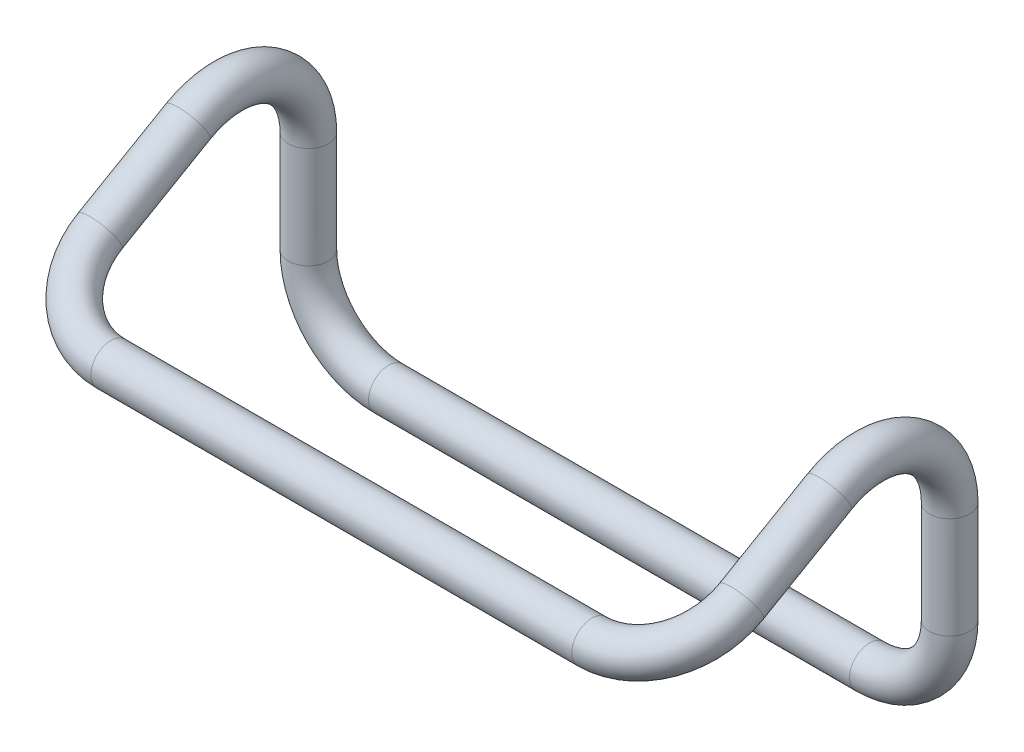
SolidWorks part; units mm, degrees
ref_plane "前视基准面" through (0, 0, 0) normal (0, 0, 1) x (1, 0, 0)
ref_plane "上视基准面" through (0, 0, 0) normal (0, 1, 0) x (1, 0, 0)
ref_plane "右视基准面" through (0, 0, 0) normal (1, 0, 0) x (0, 0, -1)
other "Configuration Table"
sketch3d "3D草图2"
  line L0 (20, 0, 0) -> (140, 0, 0)
  line L1 (160, 10, -17.3205) -> (160, 22.6795, -39.282)
  line L2 (160, 5.359, -69.282) -> (160, -20, -69.282)
  line L3 (140, -40, -69.282) -> (20, -40, -69.282)
  line L4 (0, -20, -69.282) -> (0, 5.359, -69.282)
  line L5 (0, 22.6795, -39.282) -> (0, 10, -17.3205)
  arc A0 (0, 5.359, -69.282) -> (0, 22.6795, -39.282) centre (0, 5.359, -49.282) ccw
  arc A1 (20, -40, -69.282) -> (0, -20, -69.282) centre (20, -20, -69.282) ccw
  arc A2 (160, -20, -69.282) -> (140, -40, -69.282) centre (140, -20, -69.282) ccw
  arc A3 (160, 22.6795, -39.282) -> (160, 5.359, -69.282) centre (160, 5.359, -49.282) ccw
  arc A4 (140, 0, 0) -> (160, 10, -17.3205) centre (140, 10, -17.3205) ccw
  arc A5 (20, 0, 0) -> (0, 10, -17.3205) centre (20, 10, -17.3205) ccw
  point P7 (0, 0, 0)
  point P10 (0, 40, -69.282)
  point P11 (20, 5.359, -49.282)
  point P14 (0, -40, -69.282)
  point P15 (20, -20, -89.282)
  point P18 (160, -40, -69.282)
  point P19 (140, -20, -89.282)
  point P22 (160, 40, -69.282)
  point P23 (140, 5.359, -49.282)
  point P26 (160, 0, 0)
  point P27 (140, 27.3205, -7.3205)
  point P30 (0, 0, 0)
  point P31 (20, -7.3205, -27.3205)
  dimension "D7" = 20
  dimension "D1" = 160
  dimension "D2" = 60
  dimension "D3" = 80
  dimension "D4" = 60
  dimension "D5" = 80
  dimension "D6" = 80
sweep "扫描3" add path "3D草图2" circular profile diameter 10 parameters "D3"=10
